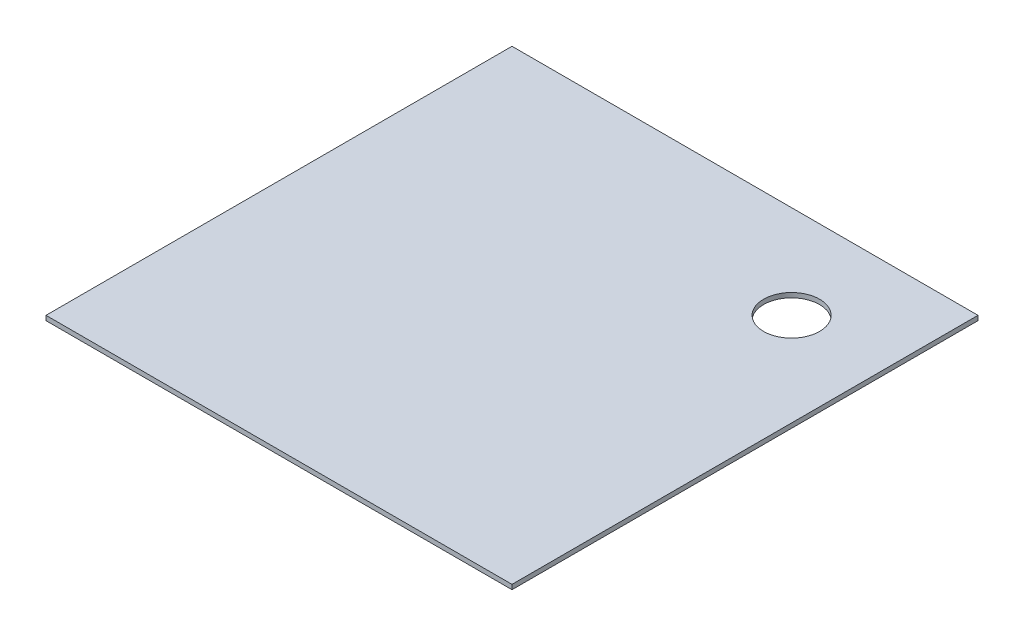
SolidWorks part; units mm, degrees
ref_plane "Front Plane" through (0, 0, 0) normal (0, 0, 1) x (1, 0, 0)
ref_plane "Top Plane" through (0, 0, 0) normal (0, 1, 0) x (1, 0, 0)
ref_plane "Right Plane" through (0, 0, 0) normal (1, 0, 0) x (0, 0, -1)
sketch "Sketch1" plane through (0, 0, 0) normal (0, 1, 0) x (1, 0, 0)
  line L1 (-25, -25) -> (25, -25)
  line L2 (-25, -25) -> (-25, 25)
  line L3 (-25, 25) -> (25, 25)
  line L4 (25, -25) -> (25, 25)
  line L5 (-25, -25) -> (25, 25) construction
  line L6 (-25, 25) -> (25, -25) construction
  circle A0 centre (15, 15) radius 3
  point P0 (0, 0)
  point P8 (0, 0)
  point P9 (0, 0)
  point P11 (-10.4843, -10.4843)
  point P12 (30.1075, 30.1075)
  point P13 (-9.0652, 0.8909)
  dimension "D2" = 6
  dimension "D1" = 50
  dimension "D3" = 10
extrude "Boss-Extrude1" add sketch "Sketch1" along normal mid plane 0.5
